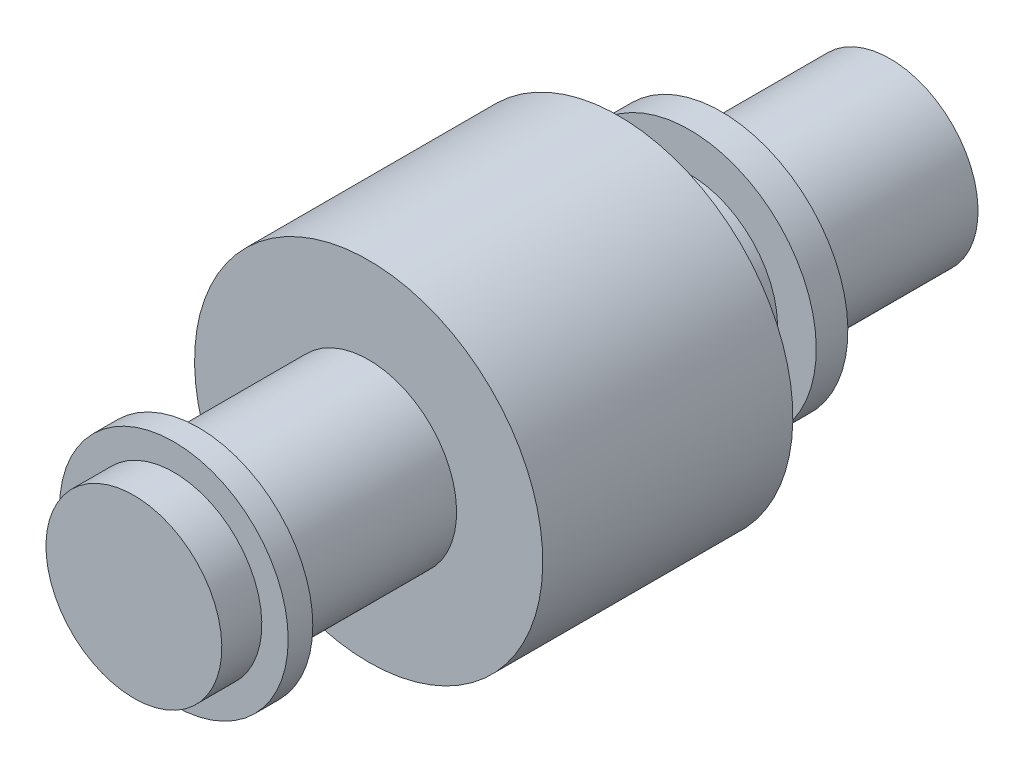
SolidWorks part; units mm, degrees
material "Cast Carbon Steel"
ref_plane "X-Y Datum" through (0, 0, 0) normal (0, 0, 1) x (1, 0, 0)
ref_plane "X-Z Datum" through (0, 0, 0) normal (0, 1, 0) x (1, 0, 0)
ref_plane "Y-Z Datum" through (0, 0, 0) normal (1, 0, 0) x (0, 0, -1)
sketch "Sketch1" plane through (0, 0, 0) normal (1, 0, 0) x (0, 0, -1)
  line L0 (-107.5004, 0) -> (107.5004, 0)
  line L1 (-96.1314, 32.4993) -> (-89.1311, 32.4993)
  line L2 (-96.1314, -32.4993) -> (-89.1311, -32.4993)
  line L3 (-96.1314, 32.4993) -> (-96.1314, -32.4993)
  line L4 (-107.5004, 24.9999) -> (-107.5004, -24.9999)
  line L5 (107.5004, 25) -> (107.5004, -24.9999)
  line L6 (-107.5004, -24.9999) -> (107.5004, -24.9999)
  line L7 (-107.5004, 24.9999) -> (107.5004, 25)
  line L8 (-89.1311, -32.4993) -> (-89.1311, 32.4993)
  line L9 (59.4944, 35.9994) -> (59.4944, -35.9994)
  line L10 (59.4944, 35.9994) -> (50.5028, 35.9994)
  line L11 (59.4944, -35.9994) -> (50.5028, -35.9994)
  line L12 (50.5028, -35.9994) -> (50.5028, 35.9994)
  line L13 (-40.7518, 49.4995) -> (-40.7518, -49.4995)
  line L14 (30.353, 49.4995) -> (30.353, -49.4995)
  line L15 (-40.7518, 49.4995) -> (30.353, 49.4995)
  line L16 (-40.7518, -49.4995) -> (30.353, -49.4995)
  point P4 (0, 0)
  point P12 (-107.5004, 0)
  point P15 (107.5004, 0)
  point P16 (-96.1314, 0)
  point P18 (59.4944, 0)
  point P23 (-40.7518, 0)
  point P26 (30.353, 0)
  dimension "D1" = 215.0008
  dimension "D2" = 11.369
  dimension "D3" = 7.0002
  dimension "D4" = 49.9999
  dimension "D5" = 64.9986
  dimension "D6" = 48.006
  dimension "D7" = 8.9916
  dimension "D8" = 71.9988
  dimension "D9" = 48.3794
  dimension "D10" = 20.1498
  dimension "D11" = 98.999
revolve "Revolve1" add sketch "Sketch1" angle 360 about L0
sketch "Sketch2" plane through (0, 0, -30.353) normal (0, 0, -1) x (-1, 0, 0)
  circle A0 centre (0, 0) radius 43.561 construction
  circle A1 centre (0, 43.561) radius 3.3
  point P3 (0, 43.561)
  dimension "D1" = 87.122
  dimension "D2" = 6.6
extrude "Cut-Extrude1" cut sketch "Sketch2" against normal blind 9.525 contours A0 A1 | A0 A1
pattern_circular "CirPattern2" count 12 over 360 about axis through (0, 0, 0) along (0, 0, 1) of "Cut-Extrude1"
